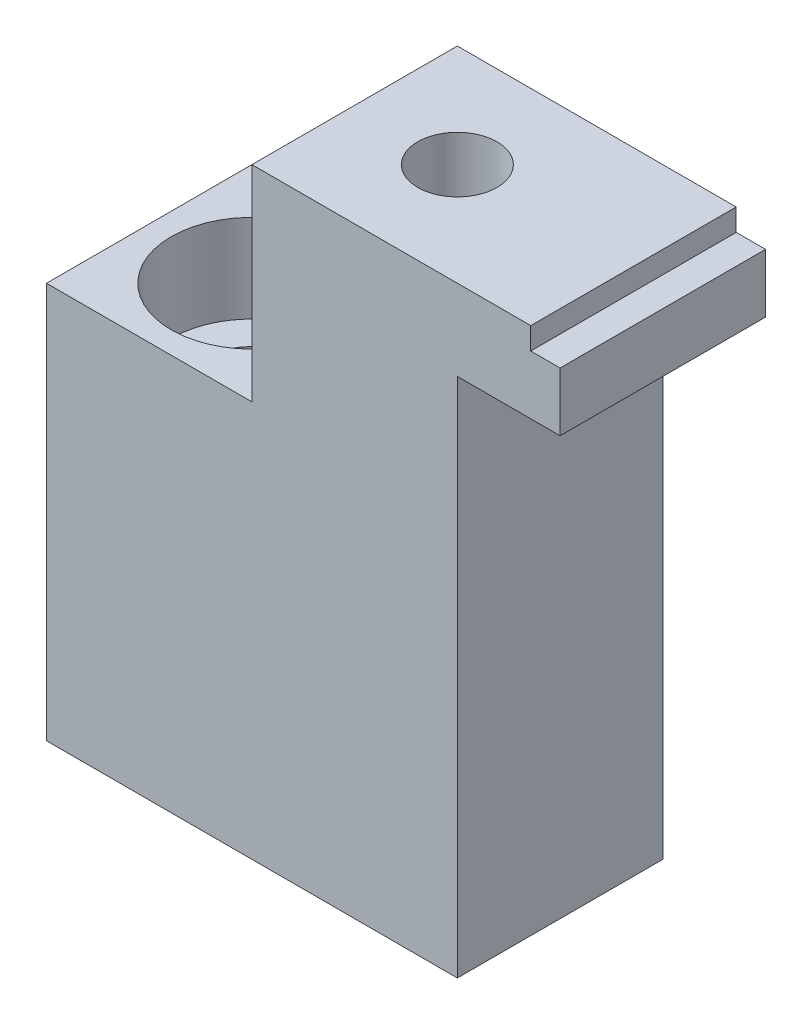
SolidWorks part; units mm, degrees
ref_plane "Alzado" through (0, 0, 0) normal (0, 0, 1) x (1, 0, 0)
ref_plane "Planta" through (0, 0, 0) normal (0, 1, 0) x (1, 0, 0)
ref_plane "Vista lateral" through (0, 0, 0) normal (1, 0, 0) x (0, 0, -1)
sketch "Croquis1" plane through (0, 0, 0) normal (0, 0, 1) x (1, 0, 0)
  line L0 (10.5, 15.75) -> (10.5, 16.25) construction
  line L1 (0, 0) -> (4, 0)
  line L2 (0, 9.5) -> (0, 16.5)
  line L4 (7, 0) -> (7, 13.75)
  line L9 (9.5, 15.75) -> (10.5, 15.75)
  line L12 (10.5, 15.75) -> (10.5, 13.75)
  line L13 (10.5, 16) -> (7, 16) construction
  line L15 (7, 13.75) -> (7, 16.5) construction
  line L16 (0, 9.5) -> (0, 0) construction
  line L17 (3.5, 0) -> (3.5, 16.5) construction
  line L18 (7, 16.5) -> (0, 16.5)
  line L21 (7, 16.5) -> (9.5, 16.5)
  line L22 (9.5, 15.75) -> (9.5, 16.5)
  line L25 (7, 13.75) -> (10.5, 13.75)
  line L27 (0, 0) -> (-7, 0)
  line L29 (0, 9.5) -> (-7, 9.5)
  line L30 (-7, 0) -> (-7, 9.5)
  line L31 (-3.5, 9.5) -> (-3.5, 0) construction
  line L32 (4, 0) -> (7, 0) construction
  line L34 (7, 0) -> (7, -4)
  line L35 (7, -4) -> (4, -4)
  line L36 (4, 0) -> (4, -4)
  line L37 (0, 13) -> (3.5, 13) construction
  line L38 (3.5, 13) -> (7, 13) construction
  dimension "D1" = 16.5
  dimension "D2" = 7
  dimension "D3" = 0.5
  dimension "D4" = 16
  dimension "D5" = 2
  dimension "D6" = 7
  dimension "D7" = 1
  dimension "D8" = 9.5
  dimension "D9" = 7
  dimension "D10" = 7.5
  dimension "D11" = 4
extrude "Saliente-Extruir1" add sketch "Croquis1" along normal blind 7
sketch "Croquis4" plane through (0, 16.5, 0) normal (0, 1, 0) x (1, 0, 0)
  line L0 (0, 0) -> (7, -7) construction
  line L1 (7, -7) -> (7, 0) construction
  line L2 (9.5, -7) -> (0, -7) construction
  circle A0 centre (3.5, -3.5) radius 1.35
  dimension "D1" = 2.7
extrude "Cortar-Extruir1" cut sketch "Croquis4" against normal blind 13.5
sketch "Croquis5" plane through (0, 9.5, 0) normal (0, 1, 0) x (1, 0, 0)
  line L0 (-7, 0) -> (0, -7) construction
  circle A0 centre (-3.5, -3.5) radius 1.6
  dimension "D1" = 3.2
extrude "Cortar-Extruir2" cut sketch "Croquis5" against normal blind 13.9
sketch "Croquis6" plane through (0, 9.5, 0) normal (0, 1, 0) x (1, 0, 0)
  circle A0 centre (-3.5, -3.5) radius 2.75
  dimension "D1" = 5.5
extrude "Cortar-Extruir3" cut sketch "Croquis6" against normal blind 3
sketch "Croquis7" plane through (0, 0, 0) normal (0, -1, 0) x (1, 0, 0)
  line L4 (-7, 0) -> (4, 0)
  line L5 (4, 0) -> (4, 7)
  line L6 (4, 7) -> (-7, 7)
  line L7 (-7, 7) -> (-7, 0)
  line L8 (-7, 0) -> (4, 0)
  line L9 (4, 0) -> (4, 7)
  line L10 (4, 7) -> (-7, 7)
  line L11 (-7, 7) -> (-7, 0)
  circle A0 centre (-3.5, 3.5) radius 1.6 construction
  circle A1 centre (-3.5, 3.5) radius 1.6
  dimension "D1" = 0
extrude "Saliente-Extruir2" add sketch "Croquis7" along normal up to surface (4 mm away) up to face at (5.5, -4, 3.5)
